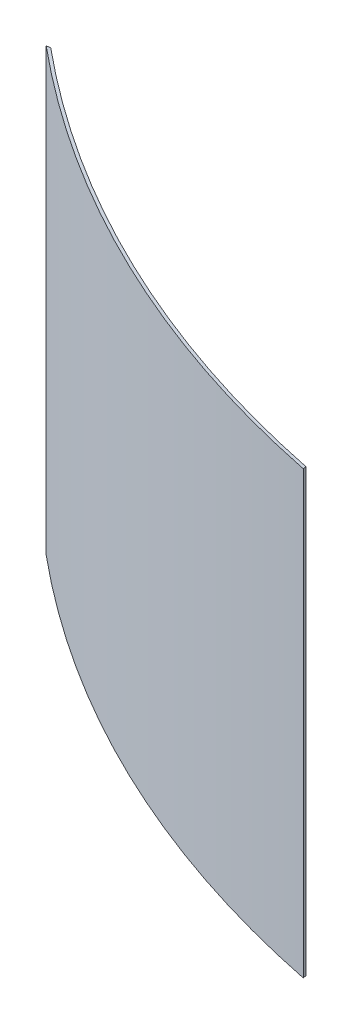
SolidWorks part; units mm, degrees
ref_plane "Front Plane" through (0, 0, 0) normal (0, 0, 1) x (1, 0, 0)
ref_plane "Top Plane" through (0, 0, 0) normal (0, 1, 0) x (1, 0, 0)
ref_plane "Right Plane" through (0, 0, 0) normal (1, 0, 0) x (0, 0, -1)
sketch "Sketch1" plane through (0, 0, 0) normal (0, 1, 0) x (1, 0, 0)
  circle A0 centre (0, 0) radius 51.0298
  circle A1 centre (0, 0) radius 50.8958
  dimension "D1" = 102.0595
extrude "Boss-Extrude1" add sketch "Sketch1" along normal blind 20
sketch "Sketch2" plane through (0, 0, 0) normal (0, 1, 0) x (1, 0, 0)
  spline S0 degree 3 poles (-65.4681, 4.6604) (-48.0498, -48.7283) (-8.7511, -27.5886) (20.5453, -14.8071) (86.6752, -3.7978) (38.1721, 77.4698) (-39.91, 55.8098) (-65.4681, 4.6604) (-48.0498, -48.7283) (-8.7511, -27.5886) knots -0.516094 -0.246811 -0.15741 0 0.044308 0.194241 0.328567 0.483906 0.753189 0.84259 1 1.044308 1.194241 1.328567 only from (-34.9047, -39.5592) to (-34.9047, -39.5592)
extrude "Cut-Extrude1" cut sketch "Sketch2" along normal blind 50
sketch "Sketch3" plane through (0, 0, 0) normal (0, 1, 0) x (1, 0, 0)
  spline S0 degree 3 poles (57.3533, 23.4316) (16.7463, -22.0441) (-4.1792, -74.1135) (71.7519, -51.3835) (57.3533, 23.4316) (16.7463, -22.0441) (-4.1792, -74.1135) knots -0.834191 -0.525852 -0.289541 0 0.165809 0.474148 0.710459 1 1.165809 1.474148 1.710459 only from (15.2463, -30.6272) to (15.2463, -30.6272)
extrude "Cut-Extrude3" cut sketch "Sketch3" along normal blind 50
sketch "Sketch4" plane through (0, 0, 0) normal (0, 1, 0) x (1, 0, 0)
  spline S0 degree 3 poles (4.5281, -45.3516) (-13.0907, -39.8573) (-7.545, -65.726) (26.7788, -53.5279) (4.5281, -45.3516) (-13.0907, -39.8573) (-7.545, -65.726) knots -0.801386 -0.43943 -0.223386 0 0.198614 0.56057 0.776614 1 1.198614 1.56057 1.776614 only from (-9.673, -44.5642) to (-9.673, -44.5642)
extrude "Cut-Extrude4" cut sketch "Sketch4" along normal blind 50
